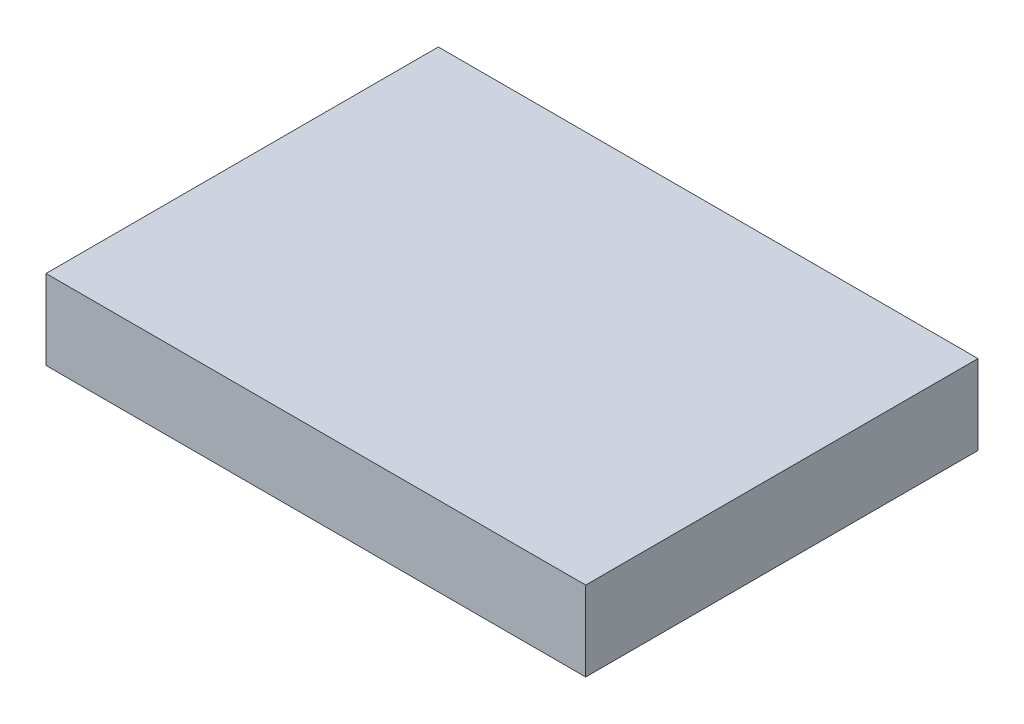
SolidWorks part; units mm, degrees
ref_plane "前视基准面" through (0, 0, 0) normal (0, 0, 1) x (1, 0, 0)
ref_plane "上视基准面" through (0, 0, 0) normal (0, 1, 0) x (1, 0, 0)
ref_plane "右视基准面" through (0, 0, 0) normal (1, 0, 0) x (0, 0, -1)
other "Configuration Table"
sketch "草图1" plane through (0, 0, 0) normal (0, 1, 0) x (1, 0, 0)
  line L1 (0, 0) -> (27.1, 0)
  line L2 (0, 0) -> (0, 19.7)
  line L3 (0, 19.7) -> (27.1, 19.7)
  line L4 (27.1, 0) -> (27.1, 19.7)
  dimension "D1" = 19.7
  dimension "D2" = 27.1
extrude "凸台-拉伸1" add sketch "草图1" along normal blind 4
